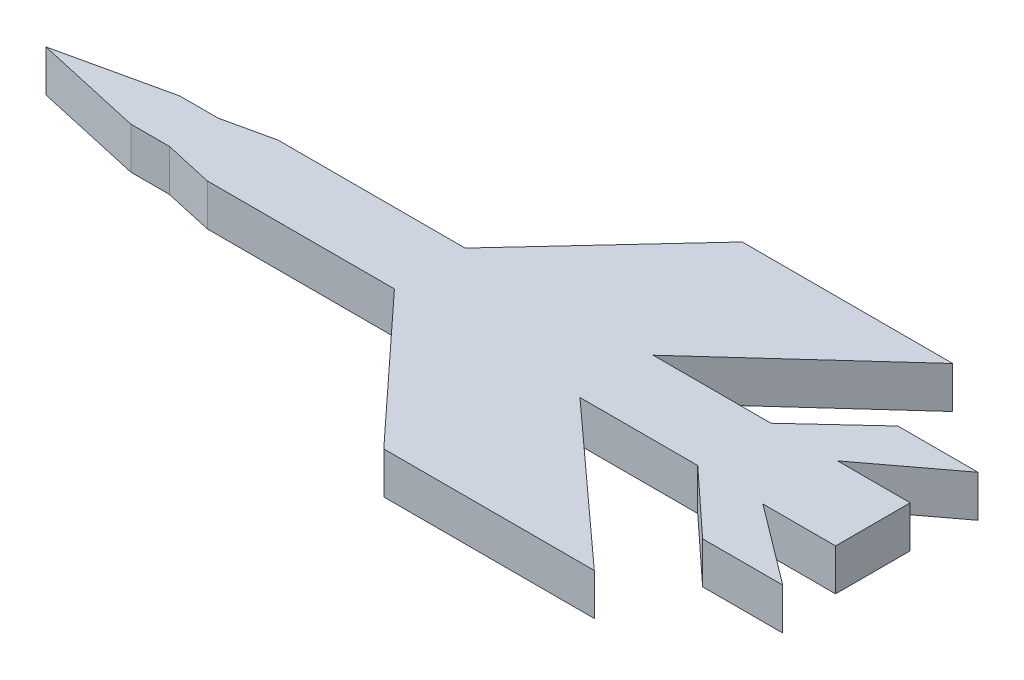
SolidWorks part; units mm, degrees
ref_plane "Front Plane" through (0, 0, 0) normal (0, 0, 1) x (1, 0, 0)
ref_plane "Top Plane" through (0, 0, 0) normal (0, 1, 0) x (1, 0, 0)
ref_plane "Right Plane" through (0, 0, 0) normal (1, 0, 0) x (0, 0, -1)
sketch "Sketch1" plane through (0, 0, 0) normal (0, 1, 0) x (1, 0, 0)
  line L0 (2.1966, 0) -> (70, 0) construction
  line L28 (2.1966, 0) -> (7.4529, 1.175)
  line L29 (2.1966, 0) -> (7.4529, -1.175)
  line L30 (7.4529, 1.175) -> (9.3036, 1.175)
  line L31 (7.4529, -1.175) -> (9.3036, -1.175)
  line L32 (9.3036, 1.175) -> (11.6511, 1.6998)
  line L33 (9.3036, -1.175) -> (11.6511, -1.6998)
  line L34 (11.6511, 1.6998) -> (20.6486, 1.6998)
  line L35 (11.6511, -1.6998) -> (20.6486, -1.6998)
  line L36 (20.6486, 1.6998) -> (27.0552, 8.6178)
  line L37 (20.6486, -1.6998) -> (27.0552, -8.6178)
  line L38 (27.0552, 8.6178) -> (37.1766, 8.6178)
  line L39 (27.0552, -8.6178) -> (37.1766, -8.6178)
  line L40 (37.1766, 8.6178) -> (29.6276, 1.76)
  line L41 (37.1766, -8.6178) -> (29.6276, -1.76)
  line L42 (29.6276, 1.76) -> (35.2925, 1.76)
  line L43 (29.6276, -1.76) -> (35.2925, -1.76)
  line L44 (35.2925, 1.76) -> (38.4617, 4.695)
  line L45 (35.2925, -1.76) -> (38.4617, -4.695)
  line L46 (38.4617, 4.695) -> (42.3138, 4.695)
  line L47 (38.4617, -4.695) -> (42.3138, -4.695)
  line L48 (42.3138, 4.695) -> (38.4617, 1.7943)
  line L49 (42.3138, -4.695) -> (38.4617, -1.7943)
  line L50 (38.4617, 1.7943) -> (41.9552, 1.7943)
  line L51 (38.4617, -1.7943) -> (41.9552, -1.7943)
  line L52 (41.9552, 1.7943) -> (41.9552, -1.7943)
  point P27 (41.9552, 0)
  point P28 (29.6276, -1.76)
  point P29 (37.2315, 8.6676)
  point P30 (27.0552, 8.6178)
  point P31 (11.6511, 1.6998)
  point P32 (5.2564, 1.175)
  point P33 (0, 0)
  point P34 (0, 0)
  point P35 (2.1966, 0)
extrude "Boss-Extrude1" add sketch "Sketch1" along normal blind 2
